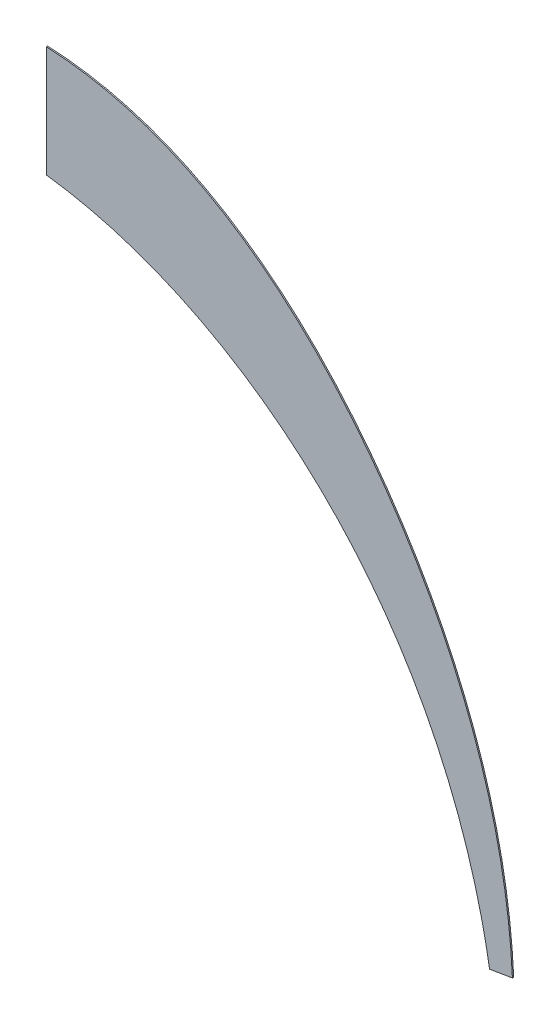
SolidWorks part; units mm, degrees
ref_plane "Front Plane" through (0, 0, 0) normal (0, 0, 1) x (1, 0, 0)
ref_plane "Top Plane" through (0, 0, 0) normal (0, 1, 0) x (1, 0, 0)
ref_plane "Right Plane" through (0, 0, 0) normal (1, 0, 0) x (0, 0, -1)
sketch "Sketch1" plane through (0, 0, 0) normal (0, 0, 1) x (1, 0, 0)
  line L0 (115.9666, -144.9958) -> (-58.5872, 272.7535) construction
  line L7 (0, 0) -> (186.6509, 0) construction
  line L8 (0, 0) -> (53.797, -15.9377) construction
  line L9 (53.797, -15.9377) -> (119.123, -65.9017) construction
  line L10 (119.123, -65.9017) -> (158.2042, -131.4148) construction
  line L11 (158.2042, -131.4148) -> (172.3633, -184.9564) construction
  line L12 (0, 0) -> (0, 43.0018)
  line L13 (180.5136, -179.0702) -> (171.668, -180.5452)
  spline S0 degree 3 poles (0, 43.0018) (58.8651, 40.423) (143.1981, -32.0859) (178.2609, -131.1261) (180.5136, -179.0702) knots 0 0 0 0 0.539711 1 1 1 1
  spline S1 degree 3 poles (172.3633, -184.9564) (165.9374, -141.6848) (129.2651, -54.6849) (46.1204, -5.801) (0, 0) knots 0 0 0 0 0.487622 1 1 1 1 construction
  spline S2 degree 3 poles (0, 0) (46.1209, -5.8036) (127.8962, -53.8712) (164.7214, -138.8496) (171.668, -180.5452) knots 0 0 0 0 0.520945 1 1 1 1
  dimension "D1" = 452.7511
  dimension "D2" = 56.1082
  dimension "D3" = 82.2428
  dimension "D4" = 76.2843
  dimension "D5" = 53.5416
  dimension "D6" = 158.228
  dimension "D7" = 159.092
  dimension "D8" = 163.995
  dimension "D9" = 16.502
extrude "Boss-Extrude1" add sketch "Sketch1" along normal blind 0.5 contours L12 S0 L13 S2
